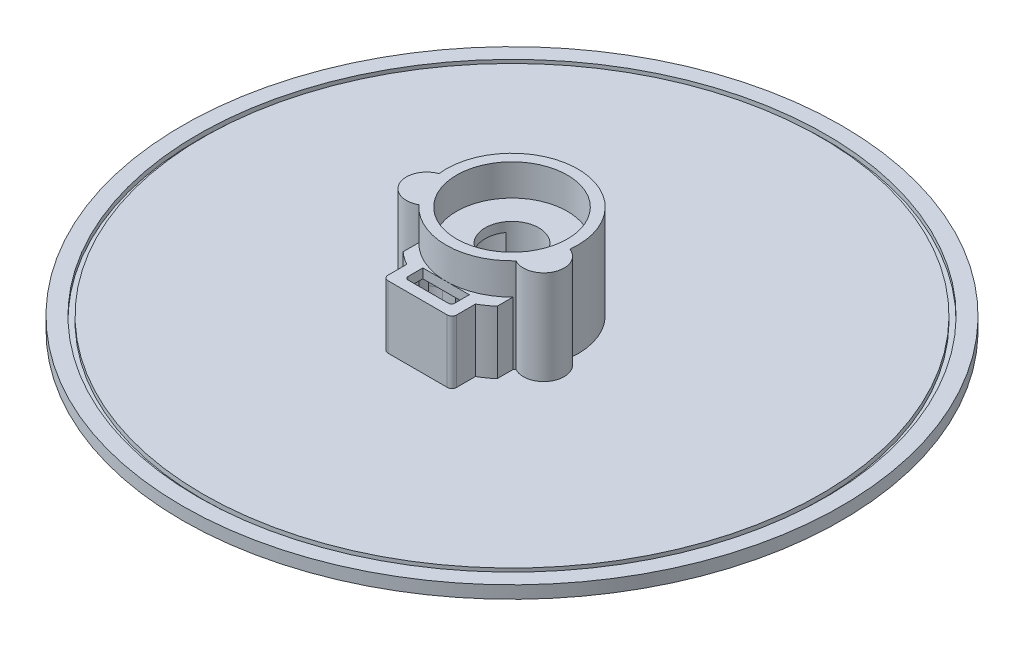
SolidWorks part; units mm, degrees
ref_plane "Front Plane" through (0, 0, 0) normal (0, 0, 1) x (1, 0, 0)
ref_plane "Top Plane" through (0, 0, 0) normal (0, 1, 0) x (1, 0, 0)
ref_plane "Right Plane" through (0, 0, 0) normal (1, 0, 0) x (0, 0, -1)
sketch "Sketch1" plane through (0, 0, 0) normal (0, 1, 0) x (1, 0, 0)
  circle A0 centre (0, 0) radius 105
  dimension "D1" = 210
extrude "Boss-Extrude1" add sketch "Sketch1" along normal blind 4
sketch "Sketch2" plane through (0, 4, 0) normal (0, 1, 0) x (1, 0, 0)
  line L2 (10.647, -20.4213) -> (10.647, -18.9495)
  line L5 (-18.6322, -12.244) -> (-14.4325, -12.244)
  line L11 (-10.647, -20.4213) -> (-10.647, -18.9495)
  line L14 (-6.7076, -28.0392) -> (6.7076, -28.0392)
  line L15 (-10.647, -20.4213) -> (-7.7723, -26.9745)
  line L17 (7.7723, -26.9745) -> (10.647, -20.4213)
  line L18 (10, -19.1803) -> (10, -17.798) construction
  line L19 (-13.5554, -4.5) -> (-17.5, -4.5) construction
  line L20 (-17.5, -11.5) -> (-13.5554, -11.5) construction
  line L21 (13.5554, -11.5) -> (17.5, -11.5) construction
  line L22 (17.5, -4.5) -> (13.5554, -4.5) construction
  line L23 (-7.3, -21.1038) -> (-7.3, -24) construction
  line L24 (-6.3, -25) -> (6.3, -25) construction
  line L25 (7.3, -24) -> (7.3, -21.1038) construction
  line L26 (-10, -19.1803) -> (-10, -17.798) construction
  line L27 (-14.1201, -3.8862) -> (-18.3611, -3.855)
  line L28 (14.1201, -3.8862) -> (18.3611, -3.855)
  line L29 (-14.1201, -3.8862) -> (14.1201, -3.8862) construction
  line L30 (0, 0) -> (0, 3.2933) construction
  line L31 (18.6322, -12.244) -> (14.4325, -12.2441)
  arc A2 (-10.647, -18.9495) -> (-14.4325, -12.244) centre (0, -8.5176) cw
  arc A18 (14.4325, -12.2441) -> (10.647, -18.9495) centre (0, -8.5176) cw
  arc A19 (6.7076, -28.0392) -> (7.7723, -26.9745) centre (6.7076, -26.9745) ccw
  circle A20 centre (0, 0) radius 4.7912 construction
  arc A21 (-7.7723, -26.9745) -> (-6.7076, -28.0392) centre (-6.7076, -26.9745) ccw
  arc A22 (-15.75, -15.4318) -> (15.75, -15.4318) centre (0, 0) ccw construction
  arc A23 (7.3, -21.1038) -> (10, -19.1803) centre (0, -8) ccw construction
  arc A24 (13.5554, -4.5) -> (-13.5554, -4.5) centre (0, -8) ccw construction
  arc A25 (-17.5, -4.5) -> (-17.5, -11.5) centre (-17.5, -8) ccw construction
  arc A26 (-13.5554, -11.5) -> (-10, -17.798) centre (0, -8) ccw construction
  arc A27 (17.5, -11.5) -> (17.5, -4.5) centre (17.5, -8) ccw construction
  arc A28 (-7.3, -24) -> (-6.3, -25) centre (-6.3, -24) ccw construction
  arc A29 (6.3, -25) -> (7.3, -24) centre (6.3, -24) ccw construction
  arc A30 (-10, -19.1803) -> (-7.3, -21.1038) centre (0, -8) ccw construction
  arc A31 (10, -17.798) -> (13.5554, -11.5) centre (0, -8) ccw construction
  arc A32 (-13.5554, -11.5) -> (-13.5554, -4.5) centre (0, -8) cw construction
  arc A33 (13.5554, -4.5) -> (13.5554, -11.5) centre (0, -8) cw construction
  circle A34 centre (0, 0) radius 4.5 construction
  circle A35 centre (17.5, -8) radius 1 construction
  circle A36 centre (-17.5, -8) radius 1 construction
  arc A37 (-18.3611, -3.855) -> (-18.6322, -12.244) centre (-18.4967, -8.0495) ccw
  arc A38 (18.3611, -3.855) -> (18.6322, -12.244) centre (18.4967, -8.0495) cw
  arc A39 (14.1201, -3.8862) -> (-14.1201, -3.8862) centre (0, -7.9741) ccw
  point P12 (0, -28.0392)
  dimension "D1" = 2
  dimension "D2" = 2
sketch "Sketch4" plane through (0, 4, 0) normal (0, 1, 0) x (1, 0, 0)
  line L0 (15, -19.6969) -> (15, -14.6969)
  line L1 (-10.95, -22.5822) -> (-10.95, -28.5822)
  line L2 (-9.45, -30.0822) -> (9.45, -30.0822)
  line L3 (10.95, -28.5822) -> (10.95, -22.5822)
  line L4 (-15, -19.6969) -> (-15, -14.6969)
  line L5 (7.4022, -25.69) -> (7.4022, -21.004)
  line L6 (-6.3882, -26.704) -> (6.3882, -26.704)
  line L7 (-7.4022, -21.004) -> (-7.4022, -25.69)
  line L8 (-7.4022, -21.004) -> (7.4022, -21.004)
  circle A1 centre (0, 0) radius 8.55
  arc A2 (-15, -14.6969) -> (-15.4729, -14.1982) centre (0, 0) cw
  arc A3 (10.95, -22.5822) -> (15, -19.6969) centre (0, -2.9264) ccw
  arc A4 (-10.95, -28.5822) -> (-9.45, -30.0822) centre (-9.45, -28.5822) ccw
  arc A5 (9.45, -30.0822) -> (10.95, -28.5822) centre (9.45, -28.5822) ccw
  arc A6 (-15, -19.6969) -> (-10.95, -22.5822) centre (0, -2.9264) ccw
  arc A7 (-20.8611, -2.4117) -> (-15.4729, -14.1982) centre (-18.6322, -8.5176) ccw
  arc A8 (15.4729, -14.1982) -> (20.8611, -2.4117) centre (18.6322, -8.5176) ccw
  arc A9 (-20.8611, -2.4117) -> (20.8611, -2.4117) centre (0, 0) cw
  arc A10 (15.4729, -14.1982) -> (15, -14.6969) centre (0, 0) cw
  arc A11 (6.3882, -26.704) -> (7.4022, -25.69) centre (6.3882, -25.69) ccw
  arc A12 (-7.4022, -25.69) -> (-6.3882, -26.704) centre (-6.3882, -25.69) ccw
  arc A13 (-15, -14.6969) -> (15, -14.6969) centre (0, 0) ccw construction
  point P36 (0, 0)
  dimension "D1" = 5
  dimension "D2" = 17.1
  dimension "D3" = 13
  dimension "D4" = 13
  dimension "D5" = 5.7
  dimension "D6" = 6
extrude "Boss-Extrude3" add sketch "Sketch4" along normal blind 20 separate body
sketch "Sketch5" plane through (0, 24, 0) normal (0, 1, 0) x (1, 0, 0)
  circle A0 centre (0, 0) radius 17.65
  arc A2 (-15.4729, -14.1982) -> (15.4729, -14.1982) centre (0, 0) ccw
  arc A3 (15.4729, -14.1982) -> (20.8611, -2.4117) centre (18.6322, -8.5176) ccw construction
  arc A4 (-20.8611, -2.4117) -> (-15.4729, -14.1982) centre (-18.6322, -8.5176) ccw construction
  arc A5 (15.4729, -14.1982) -> (20.8611, -2.4117) centre (18.6322, -8.5176) ccw
  arc A6 (-20.8611, -2.4117) -> (-15.4729, -14.1982) centre (-18.6322, -8.5176) ccw
  arc A7 (20.8611, -2.4117) -> (-20.8611, -2.4117) centre (0, 0) ccw
  dimension "D1" = 35.3
extrude "Boss-Extrude4" add sketch "Sketch5" along normal blind 10
extrude "Cut-Extrude2" cut sketch "Sketch2" against normal through all and the other way blind 17
sketch "Sketch15" plane through (0, 21, 0) normal (0, -1, 0) x (1, 0, 0)
  line L0 (-10, 19.1803) -> (-10, 17.798) construction
  line L1 (13.5554, 4.5) -> (17.5, 4.5) construction
  line L2 (17.5, 11.5) -> (13.5554, 11.5) construction
  line L3 (-13.5554, 11.5) -> (-17.5, 11.5) construction
  line L4 (-17.5, 4.5) -> (-13.5554, 4.5) construction
  line L5 (7.3, 21.1038) -> (7.3, 24) construction
  line L6 (6.3, 25) -> (-6.3, 25) construction
  line L7 (-7.3, 24) -> (-7.3, 21.1038) construction
  line L8 (10, 19.1803) -> (10, 17.798) construction
  arc A2 (-7.3, 21.1038) -> (-10, 19.1803) centre (0, 8) ccw construction
  arc A3 (-13.5554, 4.5) -> (13.5554, 4.5) centre (0, 8) ccw construction
  arc A4 (17.5, 4.5) -> (17.5, 11.5) centre (17.5, 8) ccw construction
  arc A5 (13.5554, 11.5) -> (10, 17.798) centre (0, 8) ccw construction
  arc A6 (-17.5, 11.5) -> (-17.5, 4.5) centre (-17.5, 8) ccw construction
  arc A7 (7.3, 24) -> (6.3, 25) centre (6.3, 24) ccw construction
  arc A8 (-6.3, 25) -> (-7.3, 24) centre (-6.3, 24) ccw construction
  arc A9 (10, 19.1803) -> (7.3, 21.1038) centre (0, 8) ccw construction
  arc A10 (-10, 17.798) -> (-13.5554, 11.5) centre (0, 8) ccw construction
  arc A11 (13.5554, 11.5) -> (13.5554, 4.5) centre (0, 8) cw construction
  arc A12 (-13.5554, 4.5) -> (-13.5554, 11.5) centre (0, 8) cw construction
  circle A13 centre (0, 0) radius 4.5 construction
  circle A14 centre (-17.5, 8) radius 0.85
  circle A15 centre (17.5, 8) radius 0.85
  dimension "D1" = 1.7
  dimension "D2" = 1.7
sketch "Sketch14" plane through (0, 4, 0) normal (0, 1, 0) x (1, 0, 0)
  circle A0 centre (0, 0) radius 100.05
  circle A1 centre (0, 0) radius 98.45
  dimension "D1" = 200.1
  dimension "D2" = 196.9
extrude "Cut-Extrude3" cut sketch "Sketch14" against normal blind 1.5
extrude "Cut-Extrude4" cut sketch "Sketch15" against normal blind 8
